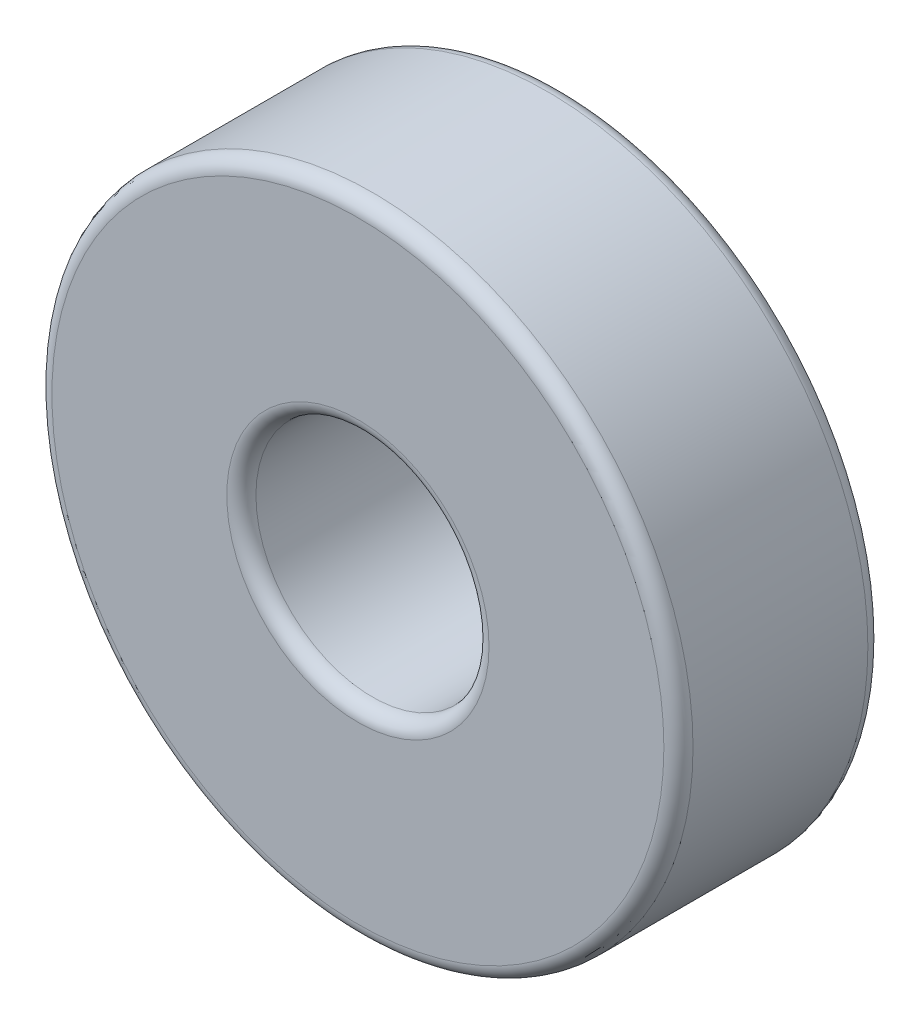
SolidWorks part; units mm, degrees
ref_plane "前视基准面" through (0, 0, 0) normal (0, 0, 1) x (1, 0, 0)
ref_plane "上视基准面" through (0, 0, 0) normal (0, 1, 0) x (1, 0, 0)
ref_plane "右视基准面" through (0, 0, 0) normal (1, 0, 0) x (0, 0, -1)
sketch "草图1" plane through (0, 0, 0) normal (0, 0, 1) x (1, 0, 0)
  circle A0 centre (0, 0) radius 11
  circle A1 centre (0, 0) radius 4
  dimension "D1" = 22
  dimension "D2" = 8
extrude "凸台-拉伸1" add sketch "草图1" along normal blind 7
fillet "圆角1" radius 0.5 4 edges at (4, 0, 7) (11, 0, 7) (4, 0, 0) (11, 0, 0)
